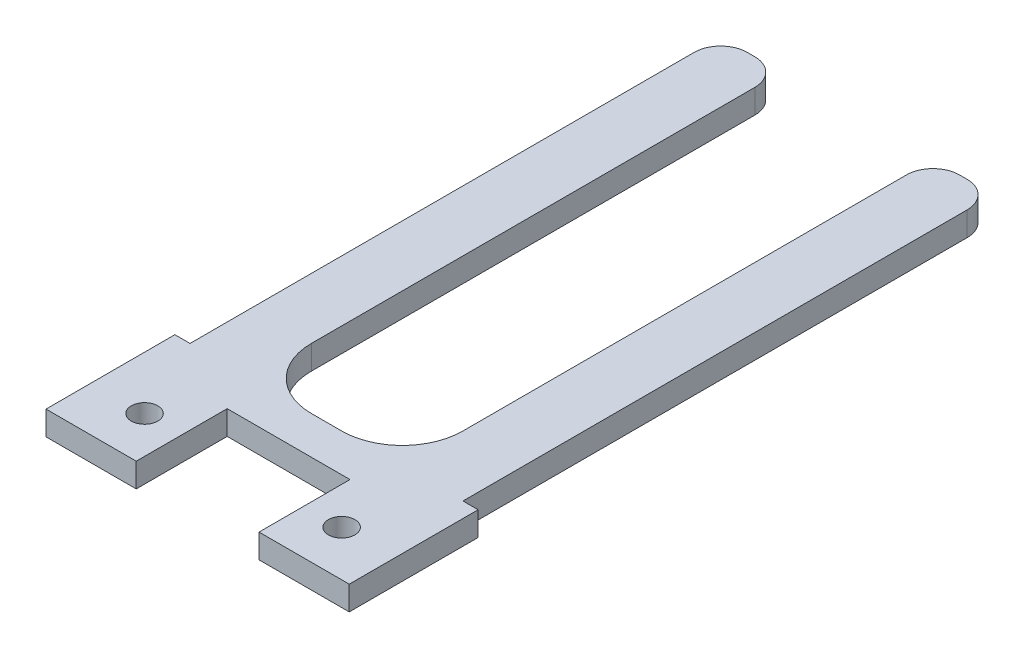
SolidWorks part; units mm, degrees
ref_plane "Alzado" through (0, 0, 0) normal (0, 0, 1) x (1, 0, 0)
ref_plane "Planta" through (0, 0, 0) normal (0, 1, 0) x (1, 0, 0)
ref_plane "Vista lateral" through (0, 0, 0) normal (1, 0, 0) x (0, 0, -1)
sketch "Croquis1" plane through (0, 0, 0) normal (0, 1, 0) x (1, 0, 0)
  line L0 (8.1, 0) -> (-8.1, 0)
  line L1 (-8.1, 0) -> (-8.1, -12)
  line L2 (-8.1, -12) -> (-20, -12)
  line L3 (-20, -12) -> (-20, 5)
  line L4 (-20, 5) -> (-18, 5)
  line L5 (-18, 5) -> (-18, 71.5)
  line L6 (-14.5, 75) -> (-13.5, 75)
  line L7 (-10, 71.5) -> (-10, 5)
  line L8 (-10, 5) -> (10, 5)
  line L9 (0, 5) -> (0, 0)
  line L10 (0, 20.5) -> (0, -26.8333) construction
  line L11 (-20, -6) -> (-8.1, -6) construction
  line L12 (10, 71.5) -> (10, 5)
  line L13 (14.5, 75) -> (13.5, 75)
  line L14 (18, 5) -> (18, 71.5)
  line L15 (20, 5) -> (18, 5)
  line L16 (20, -12) -> (20, 5)
  line L17 (8.1, -12) -> (20, -12)
  line L18 (8.1, 0) -> (8.1, -12)
  circle A0 centre (-13, -6) radius 1.75
  circle A1 centre (13, -6) radius 1.75
  arc A2 (10, 71.5) -> (13.5, 75) centre (13.5, 71.5) cw
  arc A3 (-13.5, 75) -> (-10, 71.5) centre (-13.5, 71.5) cw
  arc A4 (14.5, 75) -> (18, 71.5) centre (14.5, 71.5) cw
  arc A5 (-18, 71.5) -> (-14.5, 75) centre (-14.5, 71.5) cw
  point P29 (10, 75)
  point P32 (-10, 75)
  point P35 (18, 75)
  point P38 (-18, 75)
  point P39 (-8.1, -6)
  dimension "D8" = 3.5
  dimension "D9" = 3.5
  dimension "D1" = 8
  dimension "D2" = 11.9
  dimension "D3" = 20
  dimension "D4" = 18
  dimension "D5" = 5
  dimension "D6" = 17
  dimension "D7" = 70
  dimension "D10" = 4.9
extrude "Saliente-Extruir1" add sketch "Croquis1" along normal mid plane 3.175 contours L0 L18 L17 L16 L15 L14 L13 L12 L8 L9 A1 | L9 L8 L7 L6 L5 L4 L3 L2 L1 L0 A0
fillet "Redondeo1" radius 8 2 edges at (10, 0, -5) (-10, 0, -5)
